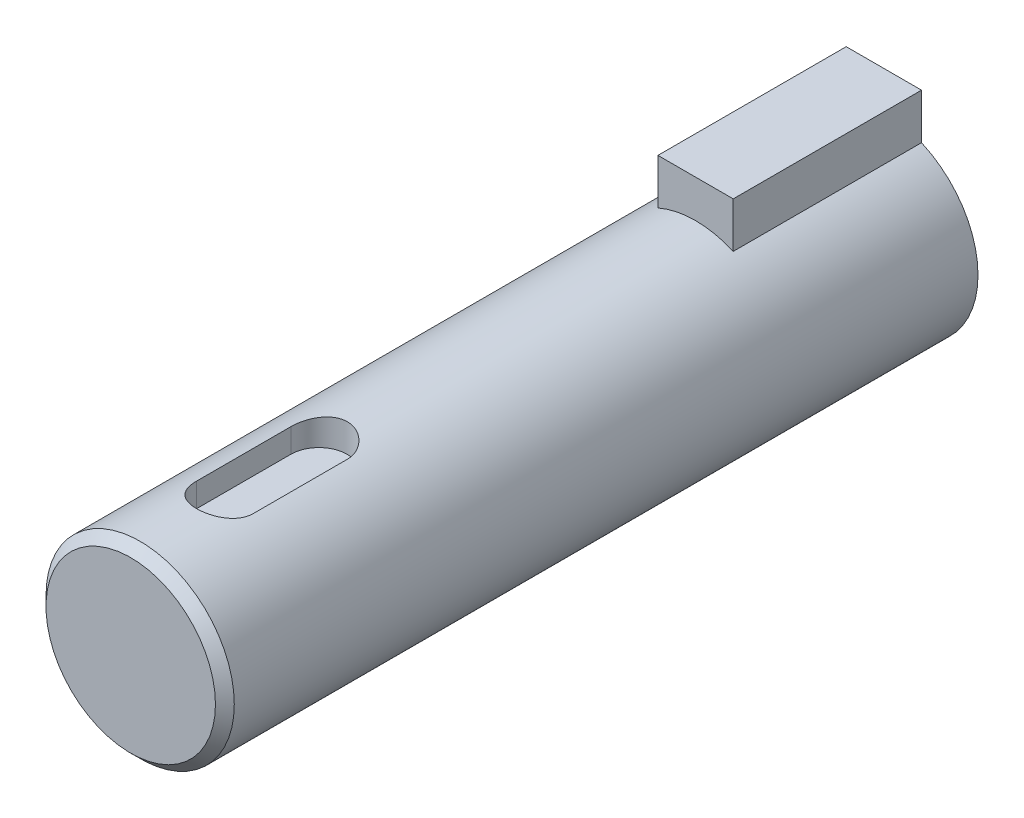
SolidWorks part; units mm, degrees
material "Alloy Steel (SS)"
ref_plane "Front " through (0, 0, 0) normal (0, 0, 1) x (1, 0, 0)
ref_plane "Top " through (0, 0, 0) normal (0, 1, 0) x (1, 0, 0)
ref_plane "Right " through (0, 0, 0) normal (1, 0, 0) x (0, 0, -1)
sketch "Sketch1" plane through (0, 0, 0) normal (0, 0, 1) x (1, 0, 0)
  line L0 (0, 0) -> (0, 11.6745) construction
  line L2 (2, 7) -> (-2, 7)
  line L3 (2, 7) -> (2, 4.5826)
  line L5 (-2, 7) -> (-2, 4.5826)
  arc A0 (-2, 4.5826) -> (2, 4.5826) centre (0, 0) ccw
  dimension "D1" = 10
  dimension "D2" = 4
  dimension "D3" = 7
extrude "Boss-Extrude1" add sketch "Sketch1" along normal blind 10
sketch "Sketch2" plane through (0, 0, 10) normal (0, 0, 1) x (1, 0, 0)
  circle A0 centre (0, 0) radius 5
extrude "Boss-Extrude2" add sketch "Sketch2" along normal blind 30
sketch "Sketch3" plane through (0, 0, 0) normal (0, 1, 0) x (1, 0, 0)
  line L0 (0, -40) -> (0, -18.9745) construction
  line L1 (-5, -40) -> (5, -40) construction
  line L2 (0, -30) -> (0, -35) construction
  line L3 (1.5, -30) -> (1.5, -35)
  line L4 (-1.5, -30) -> (-1.5, -35)
  arc A0 (1.5, -30) -> (-1.5, -30) centre (0, -30) ccw
  arc A1 (-1.5, -35) -> (1.5, -35) centre (0, -35) ccw
  point P7 (0, -32.5)
  dimension "D1" = 3
  dimension "D2" = 5
  dimension "D3" = 5
extrude "Cut-Extrude1" cut sketch "Sketch3" along normal through all from offset 3.5
chamfer "Chamfer1" distance 0.5 angle 45 1 edges at (5, 0, 40)
